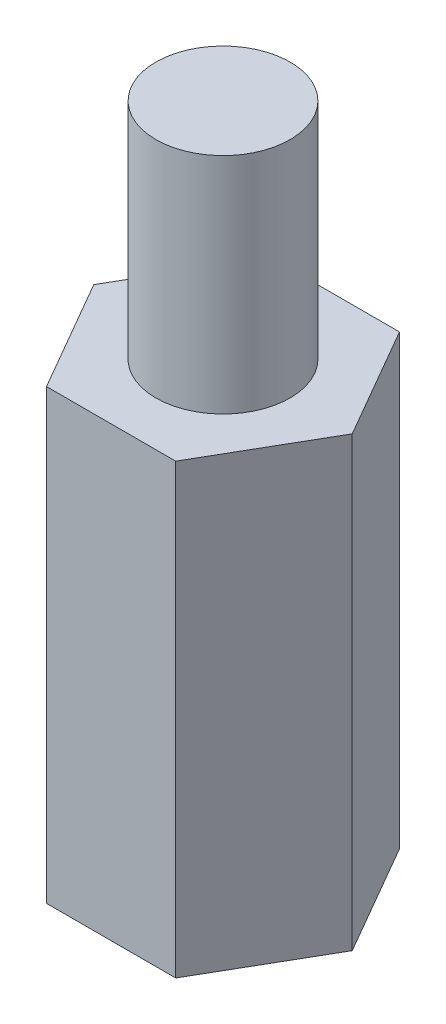
SolidWorks part; units mm, degrees
ref_plane "정면" through (0, 0, 0) normal (0, 0, 1) x (1, 0, 0)
ref_plane "윗면" through (0, 0, 0) normal (0, 1, 0) x (1, 0, 0)
ref_plane "우측면" through (0, 0, 0) normal (1, 0, 0) x (0, 0, -1)
sketch "스케치1" plane through (0, 0, 0) normal (0, 1, 0) x (1, 0, 0)
  line L1 (-1.4434, -2.5) -> (1.4434, -2.5)
  line L2 (1.4434, -2.5) -> (2.8868, 0)
  line L3 (2.8868, 0) -> (1.4434, 2.5)
  line L4 (1.4434, 2.5) -> (-1.4434, 2.5)
  line L5 (-1.4434, 2.5) -> (-2.8868, 0)
  line L6 (-2.8868, 0) -> (-1.4434, -2.5)
  circle A0 centre (0, 0) radius 2.5 construction
  dimension "D1" = 5
extrude "보스-돌출1" add sketch "스케치1" along normal blind 10
sketch "스케치2" plane through (0, 10, 0) normal (0, 1, 0) x (1, 0, 0)
  circle A0 centre (0, 0) radius 1.5
  dimension "D1" = 3
extrude "보스-돌출2" add sketch "스케치2" along normal blind 5
sketch "스케치3" plane through (0, 0, 0) normal (0, -1, 0) x (1, 0, 0)
  circle A0 centre (0, 0) radius 1.5
  dimension "D1" = 3
extrude "컷-돌출1" cut sketch "스케치3" against normal blind 6
